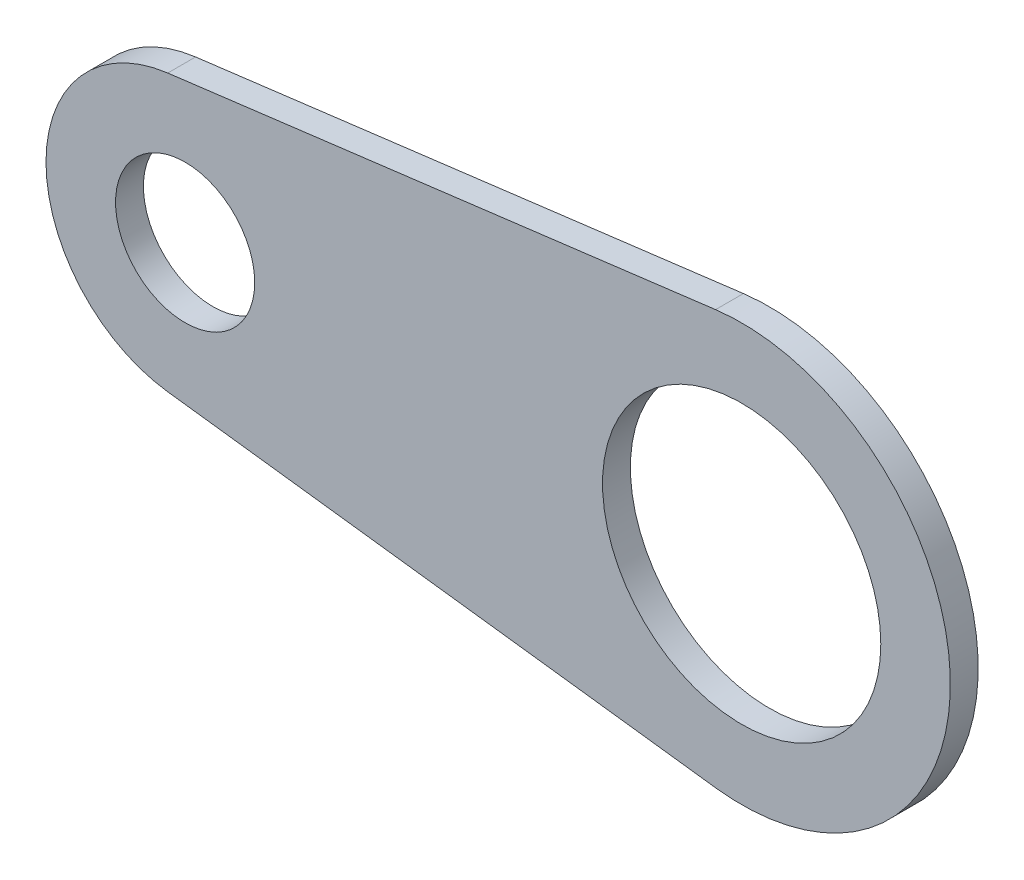
SolidWorks part; units mm, degrees
ref_plane "Спереди" through (0, 0, 0) normal (0, 0, 1) x (1, 0, 0)
ref_plane "Сверху" through (0, 0, 0) normal (0, 1, 0) x (1, 0, 0)
ref_plane "Справа" through (0, 0, 0) normal (1, 0, 0) x (0, 0, -1)
sketch "Эскиз1" plane through (0, 0, 0) normal (0, 0, 1) x (1, 0, 0)
  line L0 (-0.9375, 7.4412) -> (-20.625, 4.9608)
  line L1 (-0.9375, -7.4412) -> (-20.625, -4.9608)
  circle A0 centre (0, 0) radius 5
  arc A1 (-0.9375, -7.4412) -> (-0.9375, 7.4412) centre (0, 0) ccw
  circle A2 centre (-20, 0) radius 2.5
  arc A3 (-20.625, 4.9608) -> (-20.625, -4.9608) centre (-20, 0) ccw
  dimension "D1" = 20
  dimension "D2" = 10
  dimension "D3" = 5
  dimension "D4" = 7.5
  dimension "D5" = 5
extrude "Бобышка-Вытянуть1" add sketch "Эскиз1" along normal blind 1
